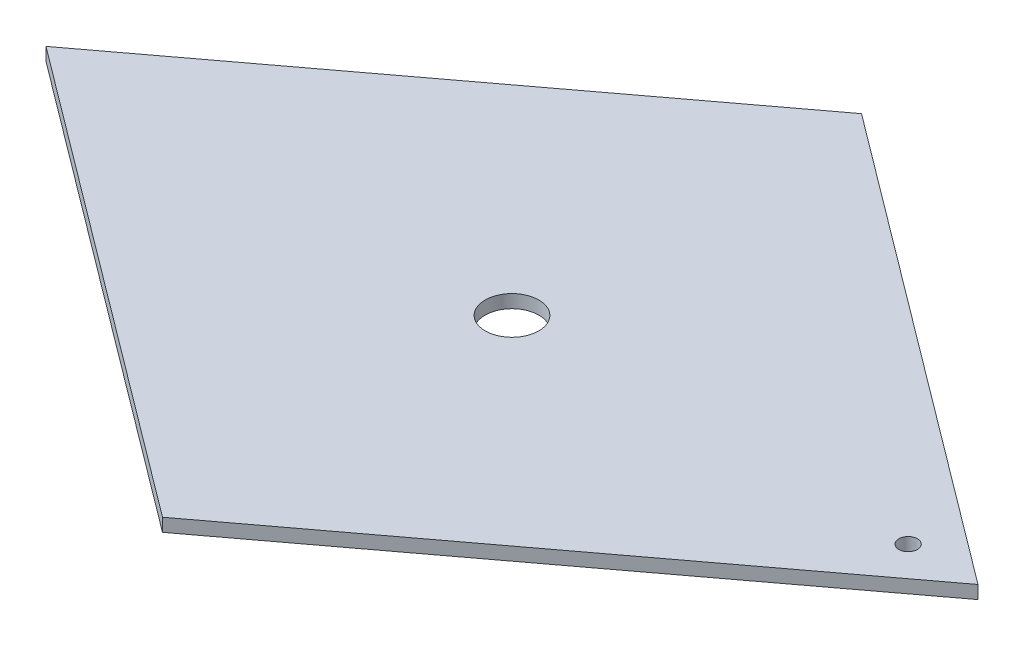
SolidWorks part; units mm, degrees
ref_plane "Front Plane" through (0, 0, 0) normal (0, 0, 1) x (1, 0, 0)
ref_plane "Top Plane" through (0, 0, 0) normal (0, 1, 0) x (1, 0, 0)
ref_plane "Right Plane" through (0, 0, 0) normal (1, 0, 0) x (0, 0, -1)
sketch "Sketch1" plane through (0, 0, 0) normal (0, 1, 0) x (1, 0, 0)
  line L20 (0, 150) -> (200, 0)
  line L21 (200, 0) -> (0, -150)
  line L22 (0, -150) -> (-200, 0)
  line L23 (-200, 0) -> (0, 150)
  circle A0 centre (0, 0) radius 11.5
  circle A1 centre (170, 0) radius 4
  dimension "D4" = 23
  dimension "D6" = 8
  dimension "D1" = 400
  dimension "D3" = 300
  dimension "D2" = 200
  dimension "D5" = 30
extrude "Boss-Extrude1" add sketch "Sketch1" along normal blind 5.63
equation "\"Side\"= 170.5"
equation "\"thick acrylic\"= 5.63"
equation "\"connect width\"= 15"
equation "\"thin acrylic\"= 2.95"
equation "\"width\"= 300"
equation "\"length\"= 400"
equation "\"D1@Boss-Extrude1\"=\"thick acrylic\""
equation "\"D1@Sketch1\"=\"length\""
equation "\"D3@Sketch1\"=\"width\""
equation "\"D2@Sketch1\"=\"length\"/2"
equation "\"lens hole\" = 23"
equation "\"D4@Sketch1\"=\"lens hole\""
